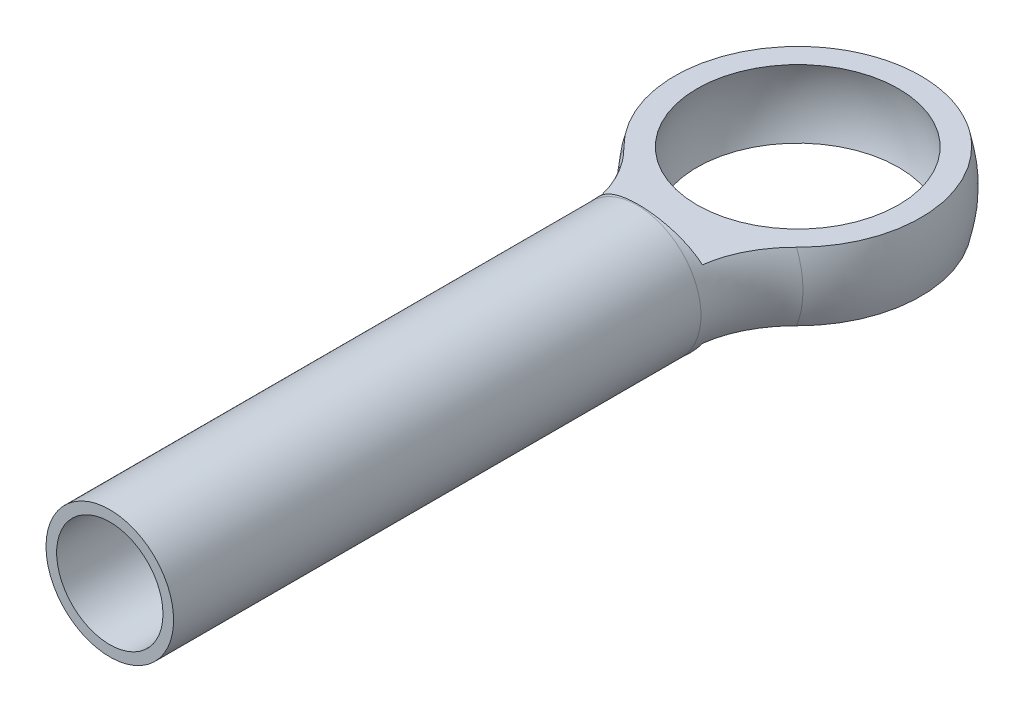
SolidWorks part; units mm, degrees
ref_plane "Front Plane" through (0, 0, 0) normal (0, 0, 1) x (1, 0, 0)
ref_plane "Top Plane" through (0, 0, 0) normal (0, 1, 0) x (1, 0, 0)
ref_plane "Right Plane" through (0, 0, 0) normal (1, 0, 0) x (0, 0, -1)
sketch "Sketch1" plane through (0, 0, 0) normal (0, 1, 0) x (1, 0, 0)
  line L3 (-1.905, -4.7941) -> (-1.905, -20.5421)
  line L4 (-1.905, -20.5421) -> (0, -20.5421)
  line L5 (0, 3.81) -> (0, -20.5421)
  line L6 (0, 3.81) -> (0, -20.5421) construction
  arc A2 (0, 3.81) -> (-2.7709, -2.615) centre (0, 0) ccw
  arc A3 (-2.7709, -2.615) -> (-1.905, -4.7941) centre (-5.08, -4.7941) cw
  dimension "D1" = 3.81
  dimension "D4" = 1.905
  dimension "D3" = 3.175
  dimension "D2" = 15.748
revolve "Revolve1" add sketch "Sketch1" angle 360 about L6
shell "Shell1" thickness 1.27
sketch "Sketch4" plane through (0, 0, 0) normal (1, 0, 0) x (0, 0, -1)
  line L0 (0, 3.175) -> (0, -3.175) construction
  line L1 (0, 3.175) -> (0, -3.175)
  arc A0 (0, -3.175) -> (0, 3.175) centre (0, 0) ccw
  dimension "D1" = 6.35
revolve "Cut-Revolve1" cut sketch "Sketch4" angle 360 about L0
sketch "Sketch2" plane through (0, 0, 20.5421) normal (0, 0, 1) x (1, 0, 0)
  circle A0 centre (0, 0) radius 1.5875
  circle A1 centre (0, 0) radius 1.905 construction
  dimension "D1" = 3.175
extrude "Cut-Extrude2" cut sketch "Sketch2" against normal blind 6.35
ref_plane "Plane1" through (0, 1.016, 0) normal (0, 1, 0) x (1, 0, 0)
sketch "Sketch3" plane through (0, 1.016, 0) normal (0, 1, 0) x (1, 0, 0)
  circle A0 centre (0, 0) radius 4.7625
  dimension "D1" = 9.525
extrude "Cut-Extrude3" cut sketch "Sketch3" along normal blind 3.81
mirror "Mirror1" about plane through (0, 0, 0) normal (0, 1, 0) of "Cut-Extrude3"
